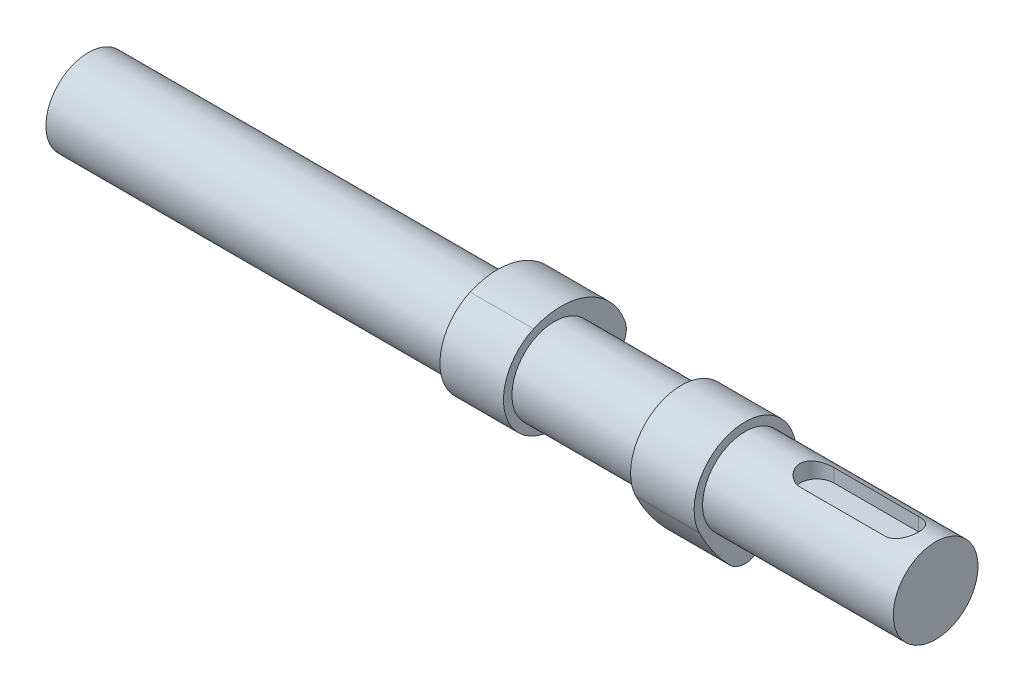
SolidWorks part; units mm, degrees
ref_plane "Front Plane" through (0, 0, 0) normal (0, 0, 1) x (1, 0, 0)
ref_plane "Top Plane" through (0, 0, 0) normal (0, 1, 0) x (1, 0, 0)
ref_plane "Right Plane" through (0, 0, 0) normal (1, 0, 0) x (0, 0, -1)
sketch "Sketch1" plane through (0, 0, 0) normal (1, 0, 0) x (0, 0, -1)
  circle A0 centre (0, 0) radius 10
  dimension "D1" = 20
extrude "Boss-Extrude1" add sketch "Sketch1" along normal blind 75 and the other way blind 125
sketch "Sketch3" plane through (0, 0, 0) normal (1, 0, 0) x (0, 0, -1)
  arc A0 (-4.875, 10.9651) -> (5.3036, -10.7644) centre (0, 0) ccw
  arc A1 (15.4821, -3.5881) -> (16.7159, 1.6614) centre (12, 0) ccw
  arc A2 (-4.875, 10.9651) -> (16.7159, 1.6614) centre (1.625, -3.655) cw
  arc A3 (5.3036, -10.7644) -> (15.4821, -3.5881) centre (-12.375, 25.1169) ccw
  dimension "D1" = 24
  dimension "D2" = 10
  dimension "D3" = 16
  dimension "D4" = 40
extrude "Boss-Extrude2" add sketch "Sketch3" against normal blind 15 from offset 15 separate body offset against normal yes
mirror "Mirror2" about plane through (0, 0, 0) normal (1, 0, 0) of bodies 102
move or copy body "Body-Move/Copy2" bodies to move or copy 105 copy no rotation origin (0, 0, 0) rotation axis (-1, 0, 0) rotation angle 90
ref_plane "Plane1" through (0, 10, 0) normal (0, 1, 0) x (1, 0, 0)
sketch "Sketch5" plane through (0, 10, 0) normal (0, 1, 0) x (1, 0, 0)
  line L0 (75, 0) -> (35.0218, 0) construction
  line L1 (75, -10) -> (75, 10) construction
  line L2 (47, 0) -> (67, 0) construction
  line L3 (47, 4) -> (67, 4)
  line L4 (47, -4) -> (67, -4)
  arc A0 (47, 4) -> (47, -4) centre (47, 0) ccw
  arc A1 (67, -4) -> (67, 4) centre (67, 0) ccw
  point P7 (57, 0)
  dimension "D3" = 4
  dimension "D1" = 20
  dimension "D2" = 8
extrude "Cut-Extrude1" cut sketch "Sketch5" against normal blind 4
